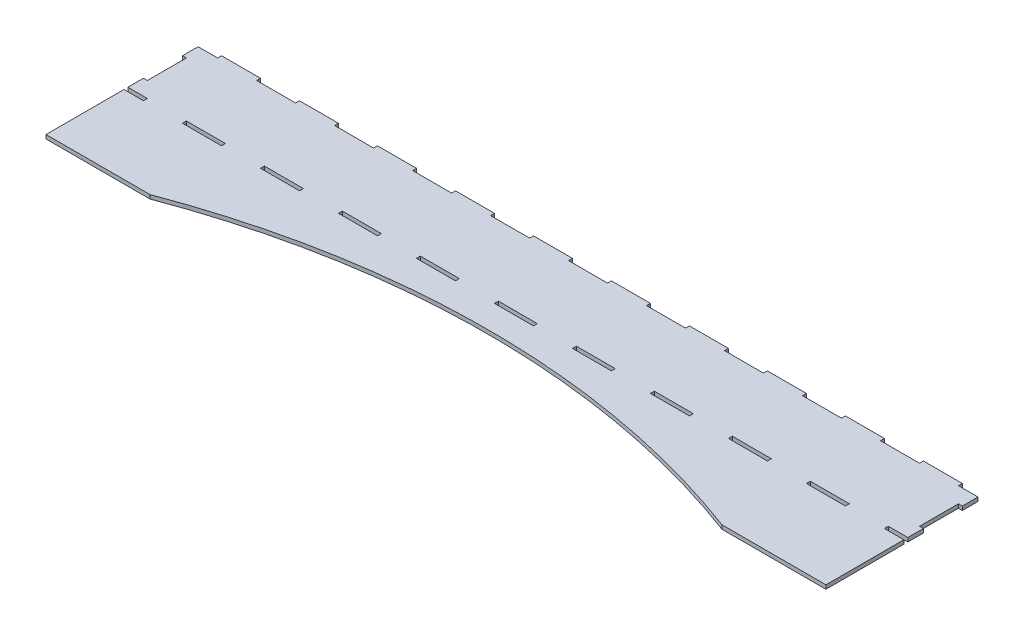
SolidWorks part; units mm, degrees
ref_plane "Front Plane" through (0, 0, 0) normal (0, 0, 1) x (1, 0, 0)
ref_plane "Top Plane" through (0, 0, 0) normal (0, 1, 0) x (1, 0, 0)
ref_plane "Right Plane" through (0, 0, 0) normal (1, 0, 0) x (0, 0, -1)
sketch "Sketch1" plane through (0, 0, 0) normal (0, 1, 0) x (1, 0, 0)
  line L1 (0, 0) -> (600, 0)
  line L2 (0, 0) -> (0, 60)
  line L3 (0, 60) -> (600, 60)
  line L4 (600, 0) -> (600, 60)
  dimension "D1" = 600
  dimension "D2" = 60
extrude "Boss-Extrude1" add sketch "Sketch1" along normal blind 3
sketch "Sketch3" plane through (0, 3, 0) normal (0, 1, 0) x (1, 0, 0)
  line L1 (0, 0) -> (600, 0)
  line L2 (0, 0) -> (0, -60)
  line L3 (0, -60) -> (600, -60)
  line L4 (600, 0) -> (600, -60)
  dimension "D1" = 60
extrude "Boss-Extrude2" add sketch "Sketch3" against normal blind 3
sketch "Sketch2" plane through (0, 3, 0) normal (0, 1, 0) x (1, 0, 0)
  line L1 (-15, 0) -> (15, 0)
  line L2 (-15, 0) -> (-15, 3)
  line L3 (-15, 3) -> (15, 3)
  line L4 (15, 0) -> (15, 3)
  line L5 (0, 60) -> (0, -60) construction
  line L6 (45, 0) -> (45, 3)
  line L7 (45, 0) -> (75, 0)
  line L8 (75, 0) -> (75, 3)
  line L9 (45, 3) -> (75, 3)
  line L10 (105, 0) -> (105, 3)
  line L11 (105, 0) -> (135, 0)
  line L12 (135, 0) -> (135, 3)
  line L13 (105, 3) -> (135, 3)
  line L14 (165, 0) -> (165, 3)
  line L15 (165, 0) -> (195, 0)
  line L16 (195, 0) -> (195, 3)
  line L17 (165, 3) -> (195, 3)
  line L18 (225, 0) -> (225, 3)
  line L19 (225, 0) -> (255, 0)
  line L20 (255, 0) -> (255, 3)
  line L21 (225, 3) -> (255, 3)
  line L22 (285, 0) -> (285, 3)
  line L23 (285, 0) -> (315, 0)
  line L24 (315, 0) -> (315, 3)
  line L25 (285, 3) -> (315, 3)
  line L26 (345, 0) -> (345, 3)
  line L27 (345, 0) -> (375, 0)
  line L28 (375, 0) -> (375, 3)
  line L29 (345, 3) -> (375, 3)
  line L30 (405, 0) -> (405, 3)
  line L31 (405, 0) -> (435, 0)
  line L32 (435, 0) -> (435, 3)
  line L33 (405, 3) -> (435, 3)
  line L34 (465, 0) -> (465, 3)
  line L35 (465, 0) -> (495, 0)
  line L36 (495, 0) -> (495, 3)
  line L37 (465, 3) -> (495, 3)
  line L38 (525, 0) -> (525, 3)
  line L39 (525, 0) -> (555, 0)
  line L40 (555, 0) -> (555, 3)
  line L41 (525, 3) -> (555, 3)
  line L42 (0, 30) -> (600, 30) construction
  line L44 (525, 57) -> (555, 57)
  line L45 (555, 60) -> (555, 57)
  line L46 (525, 60) -> (555, 60)
  line L47 (525, 60) -> (525, 57)
  line L48 (465, 57) -> (495, 57)
  line L49 (495, 60) -> (495, 57)
  line L50 (465, 60) -> (495, 60)
  line L51 (465, 60) -> (465, 57)
  line L52 (405, 57) -> (435, 57)
  line L53 (435, 60) -> (435, 57)
  line L54 (405, 60) -> (435, 60)
  line L55 (405, 60) -> (405, 57)
  line L56 (345, 57) -> (375, 57)
  line L57 (375, 60) -> (375, 57)
  line L58 (345, 60) -> (375, 60)
  line L59 (345, 60) -> (345, 57)
  line L60 (285, 57) -> (315, 57)
  line L61 (315, 60) -> (315, 57)
  line L62 (285, 60) -> (315, 60)
  line L63 (285, 60) -> (285, 57)
  line L64 (225, 57) -> (255, 57)
  line L65 (255, 60) -> (255, 57)
  line L66 (225, 60) -> (255, 60)
  line L67 (225, 60) -> (225, 57)
  line L68 (165, 57) -> (195, 57)
  line L69 (195, 60) -> (195, 57)
  line L70 (165, 60) -> (195, 60)
  line L71 (165, 60) -> (165, 57)
  line L72 (105, 57) -> (135, 57)
  line L73 (135, 60) -> (135, 57)
  line L74 (105, 60) -> (135, 60)
  line L75 (105, 60) -> (105, 57)
  line L76 (45, 57) -> (75, 57)
  line L77 (75, 60) -> (75, 57)
  line L78 (45, 60) -> (75, 60)
  line L79 (45, 60) -> (45, 57)
  line L80 (15, 60) -> (15, 57)
  line L81 (-15, 57) -> (15, 57)
  line L82 (-15, 60) -> (-15, 57)
  line L83 (-15, 60) -> (15, 60)
  line L84 (600, 60) -> (0, 60) construction
  line L85 (0, 45) -> (3, 45)
  line L86 (0, 45) -> (0, 15)
  line L87 (0, 15) -> (3, 15)
  line L88 (3, 45) -> (3, 15)
  line L89 (300, 60) -> (300, 0) construction
  line L90 (597, 45) -> (597, 15)
  line L91 (600, 15) -> (597, 15)
  line L92 (600, 45) -> (600, 15)
  line L93 (600, 45) -> (597, 45)
  line L94 (585, 0) -> (585, 3)
  line L99 (585, 0) -> (615, 0)
  line L100 (615, 0) -> (615, 3)
  line L101 (585, 3) -> (615, 3)
  line L102 (585, 60) -> (615, 60)
  line L103 (615, 60) -> (615, 57)
  line L104 (585, 57) -> (615, 57)
  line L105 (585, 60) -> (585, 57)
  dimension "D1" = 30
  dimension "D2" = 15
  dimension "D3" = 3
  dimension "D5" = 15
  dimension "D6" = 30
  dimension "D7" = 60
  dimension "D4" = 11
extrude "Cut-Extrude1" cut sketch "Sketch2" against normal blind 5
sketch "Sketch4" plane through (0, 3, 0) normal (0, 1, 0) x (1, 0, 0)
  line L0 (0, -60) -> (600, -60) construction
  line L1 (80, -60) -> (520, -60)
  arc A0 (80, -60) -> (520, -60) centre (300, -645) cw
  point P3 (300, -20)
  dimension "D3" = 40
  dimension "D1" = 80
  dimension "D2" = 80
extrude "Cut-Extrude2" cut sketch "Sketch4" against normal blind 5
